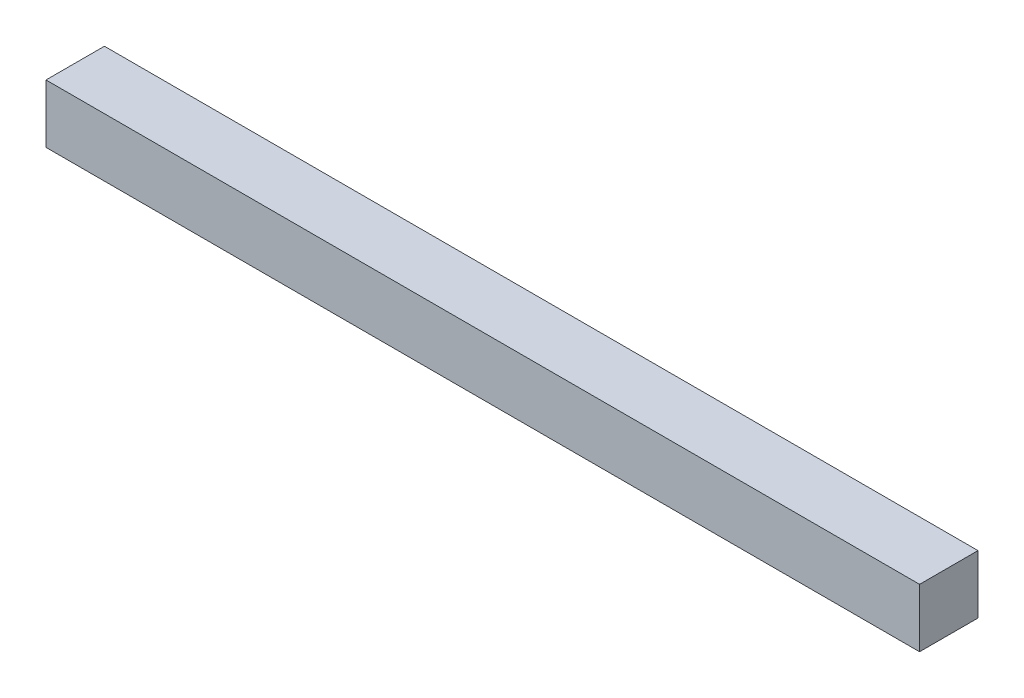
SolidWorks part; units mm, degrees
material "Nylon 6/10"
ref_plane "Front Plane" through (0, 0, 0) normal (1, 0, 0) x (0, 1, 0)
ref_plane "Top Plane" through (0, 0, 0) normal (0, 0, 1) x (0, 1, 0)
ref_plane "Right Plane" through (0, 0, 0) normal (0, 1, 0) x (-1, 0, 0)
sketch "Sketch1" plane through (0, 0, 0) normal (1, 0, 0) x (0, 1, 0)
  line L1 (-6.35, 6.35) -> (6.35, 6.35)
  line L2 (-6.35, 6.35) -> (-6.35, -6.35)
  line L3 (-6.35, -6.35) -> (6.35, -6.35)
  line L4 (6.35, 6.35) -> (6.35, -6.35)
  line L5 (-6.35, 6.35) -> (6.35, -6.35) construction
  line L6 (-6.35, -6.35) -> (6.35, 6.35) construction
  point P0 (0, 0)
  dimension "D1" = 12.7
  dimension "D2" = 12.7
extrude "Boss-Extrude1" add sketch "Sketch1" along normal blind 189.9
